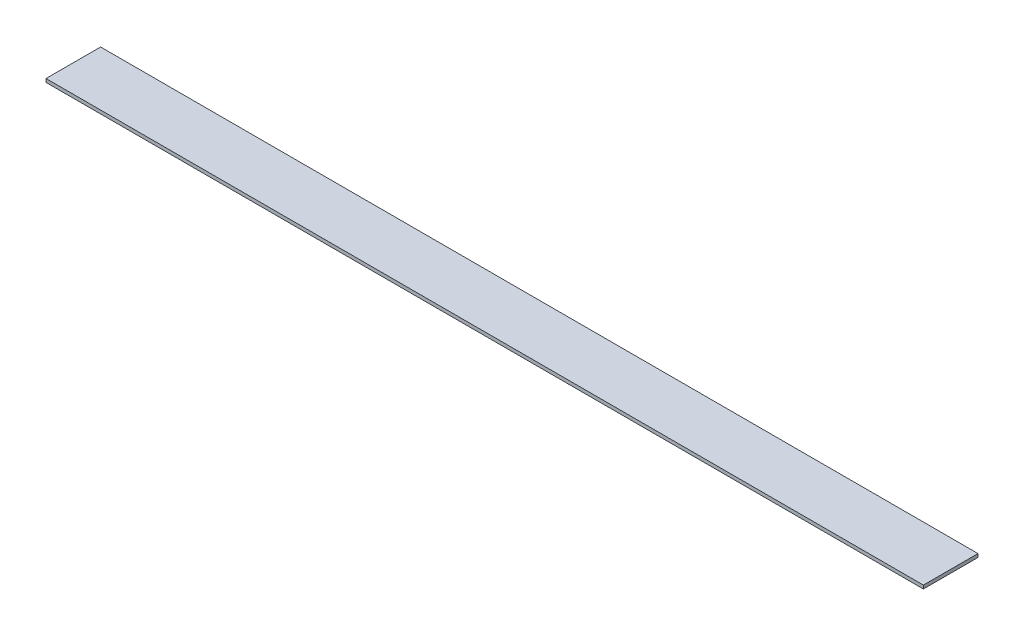
SolidWorks part; units mm, degrees
ref_plane "Front Plane" through (0, 0, 0) normal (0, 0, 1) x (1, 0, 0)
ref_plane "Top Plane" through (0, 0, 0) normal (0, 1, 0) x (1, 0, 0)
ref_plane "Right Plane" through (0, 0, 0) normal (1, 0, 0) x (0, 0, -1)
sketch "Sketch1" plane through (0, 0, 0) normal (0, 1, 0) x (1, 0, 0)
  line L1 (0, 0) -> (816.3001, 0)
  line L2 (0, 0) -> (0, 50.8)
  line L3 (0, 50.8) -> (816.3001, 50.8)
  line L4 (816.3001, 0) -> (816.3001, 50.8)
  dimension "D1" = 50.8
  dimension "D2" = 816.3001
extrude "Boss-Extrude1" add sketch "Sketch1" along normal blind 3.175
